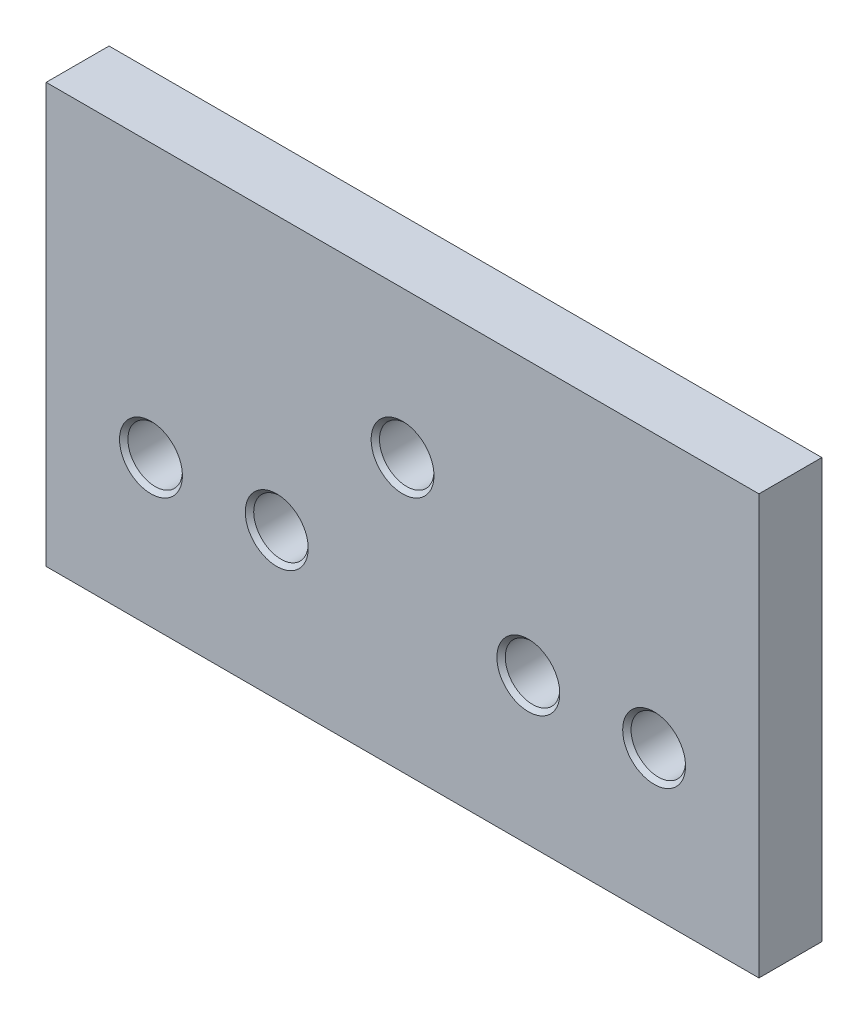
SolidWorks part; units mm, degrees
ref_plane "前基準面" through (0, 0, 0) normal (0, 0, 1) x (1, 0, 0)
ref_plane "上基準面" through (0, 0, 0) normal (0, 1, 0) x (1, 0, 0)
ref_plane "右基準面" through (0, 0, 0) normal (1, 0, 0) x (0, 0, -1)
sketch "草圖1" plane through (0, 0, 0) normal (0, 0, 1) x (1, 0, 0)
  line L0 (0, 0) -> (0, 3) construction
  line L1 (-17, -10) -> (17, -10)
  line L2 (-17, -10) -> (-17, 10)
  line L3 (-17, 10) -> (17, 10)
  line L4 (17, -10) -> (17, 10)
  line L5 (-17, -10) -> (17, 10) construction
  line L6 (-17, 10) -> (17, -10) construction
  line L7 (0, 0) -> (0, -3) construction
  line L8 (0, -3) -> (-6, -3) construction
  line L9 (-6, -3) -> (-12, -3) construction
  line L10 (0, -3) -> (6, -3) construction
  line L11 (6, -3) -> (12, -3) construction
  circle A0 centre (0, 3) radius 1.3
  circle A1 centre (-6, -3) radius 1.3
  circle A3 centre (6, -3) radius 1.3
  circle A4 centre (12, -3) radius 1.3
  circle A5 centre (-12, -3) radius 1.3
  point P0 (0, 0)
  dimension "D3" = 2.6
  dimension "D1" = 34
  dimension "D2" = 20
  dimension "D4" = 3
  dimension "D5" = 6
  dimension "D6" = 6
extrude "填料-伸長1" add sketch "草圖1" along normal blind 3
chamfer "導角1" distance 0.2 5 edges at (13.3, -3, 3) (7.3, -3, 3) (1.3, 3, 3) (-4.7, -3, 3) (-10.7, -3, 3)
